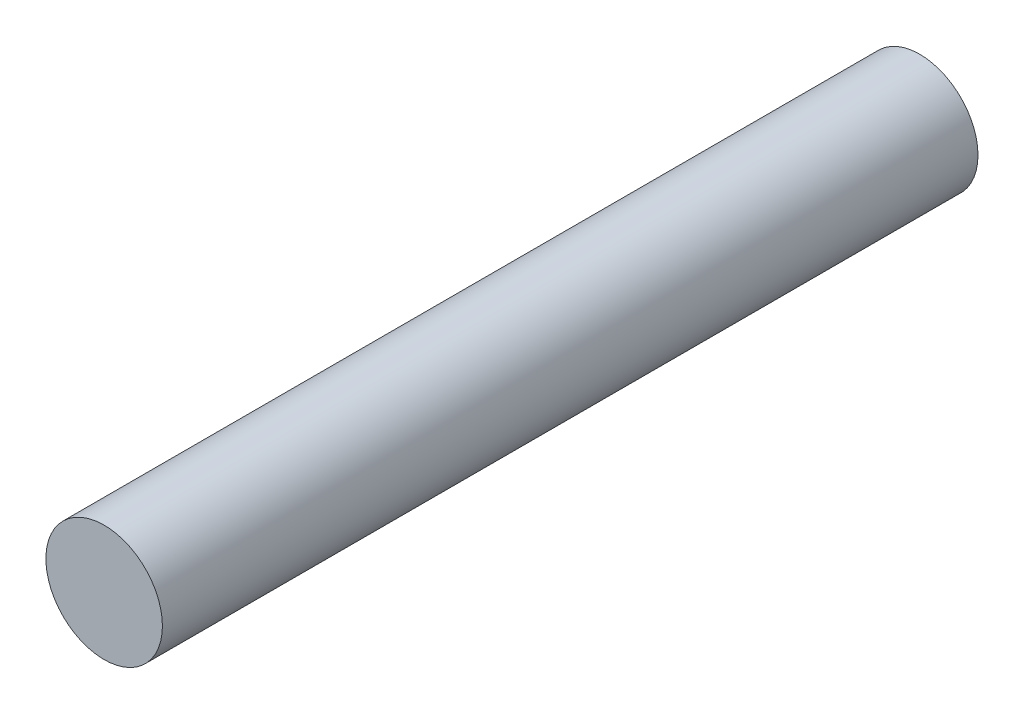
SolidWorks part; units mm, degrees
ref_plane "前视基准面" through (0, 0, 0) normal (0, 0, 1) x (1, 0, 0)
ref_plane "上视基准面" through (0, 0, 0) normal (0, 1, 0) x (1, 0, 0)
ref_plane "右视基准面" through (0, 0, 0) normal (1, 0, 0) x (0, 0, -1)
other "Configuration Table"
sketch "草图1" plane through (0, 0, 0) normal (0, 0, 1) x (1, 0, 0)
  circle A0 centre (0, 0) radius 2
extrude "轴向尺寸_28" add sketch "草图1" along normal blind 28
